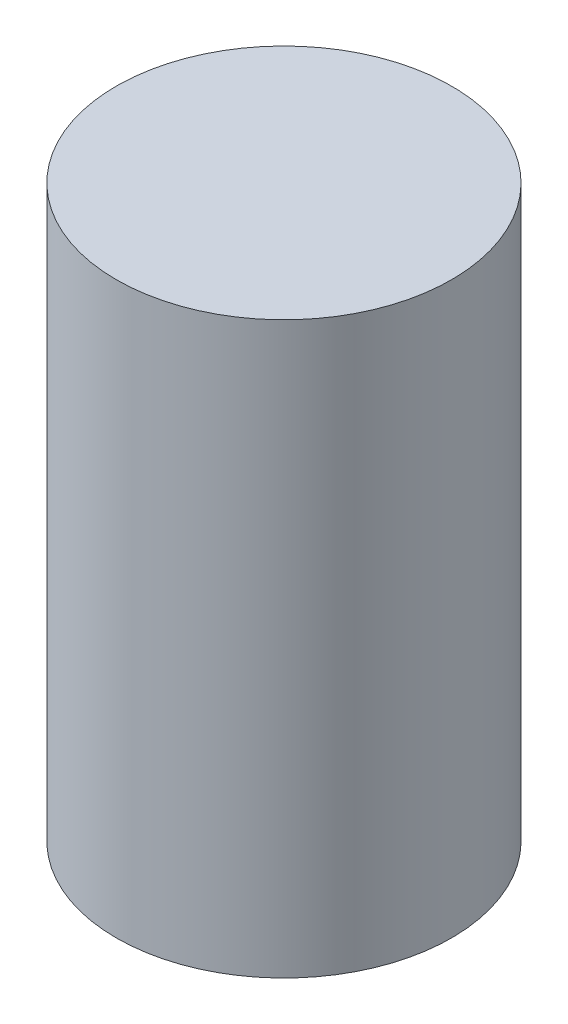
SolidWorks part; units mm, degrees
ref_plane "Front Plane" through (0, 0, 0) normal (0, 0, 1) x (1, 0, 0)
ref_plane "Top Plane" through (0, 0, 0) normal (0, 1, 0) x (1, 0, 0)
ref_plane "Right Plane" through (0, 0, 0) normal (1, 0, 0) x (0, 0, -1)
sketch "Sketch1" plane through (0, 0, 0) normal (0, 1, 0) x (1, 0, 0)
  circle A0 centre (0, 0) radius 15
  dimension "D1" = 30
extrude "Boss-Extrude1" add sketch "Sketch1" along normal blind 51
